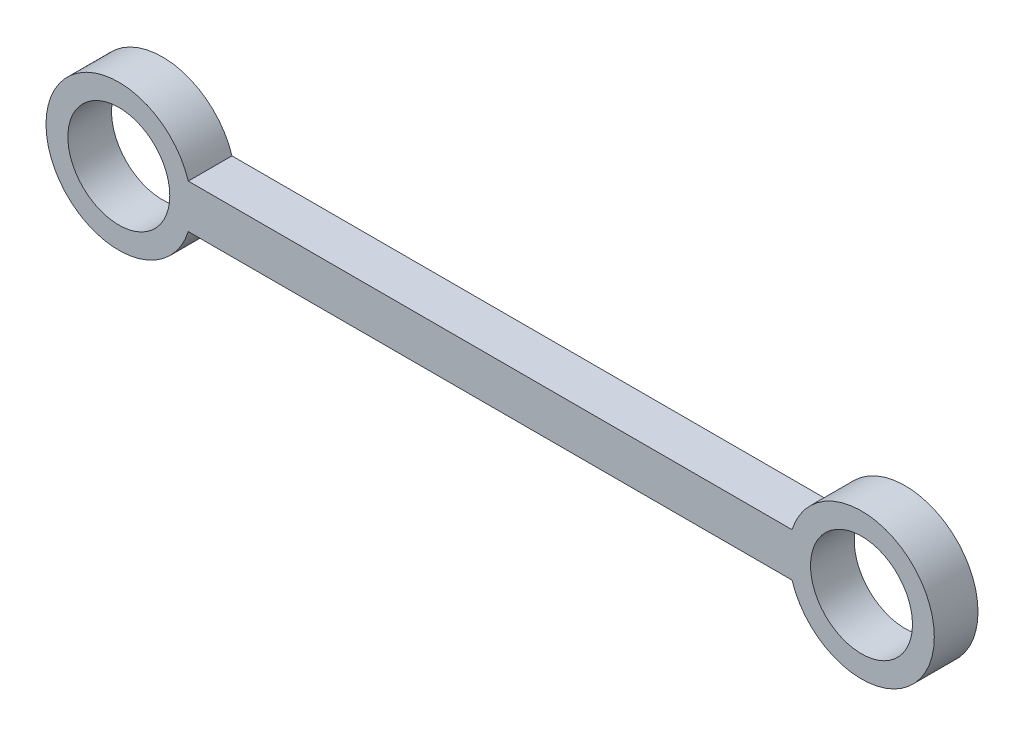
SolidWorks part; units mm, degrees
ref_plane "Front Plane" through (0, 0, 0) normal (0, 0, 1) x (1, 0, 0)
ref_plane "Top Plane" through (0, 0, 0) normal (0, 1, 0) x (1, 0, 0)
ref_plane "Right Plane" through (0, 0, 0) normal (1, 0, 0) x (0, 0, -1)
sketch "Sketch1" plane through (0, 0, 0) normal (0, 0, 1) x (1, 0, 0)
  line L1 (10.3652, 0.75) -> (-10.3652, 0.75)
  line L2 (10.3652, -0.75) -> (-10.3652, -0.75)
  circle A0 centre (12.75, 0) radius 1.75
  circle A1 centre (-12.75, 0) radius 1.75
  arc A2 (10.3652, -0.75) -> (10.3652, 0.75) centre (12.75, 0) ccw
  arc A3 (-10.3652, 0.75) -> (-10.3652, -0.75) centre (-12.75, 0) ccw
  point P0 (12.75, 0.75)
  point P4 (0, 0)
  point P6 (-12.75, 0.75)
  point P7 (12.75, -0.75)
  point P8 (-12.75, -0.75)
extrude "Boss-Extrude1" add sketch "Sketch1" along normal blind 1.5
